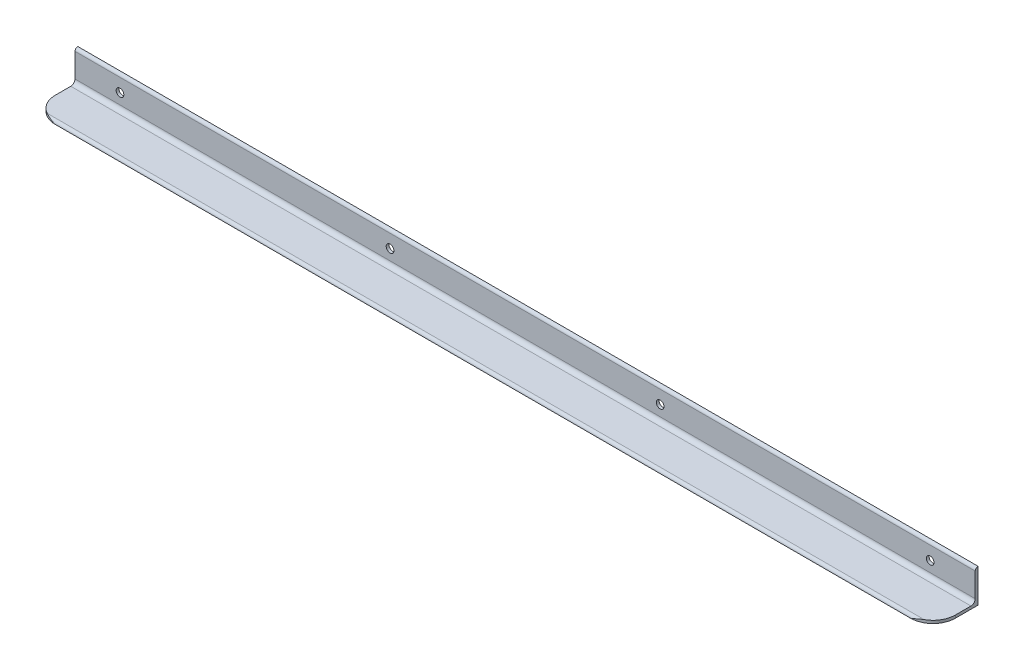
SolidWorks part; units mm, degrees
ref_plane "Front Plane" through (0, 0, 0) normal (0, 0, 1) x (1, 0, 0)
ref_plane "Top Plane" through (0, 0, 0) normal (0, 1, 0) x (1, 0, 0)
ref_plane "Right Plane" through (0, 0, 0) normal (1, 0, 0) x (0, 0, -1)
sketch "Sketch1" plane through (0, 0, 0) normal (0, 0, 1) x (1, 0, 0)
  line L0 (-508, 0) -> (508, 0)
  point P4 (0, 0)
  dimension "D1" = 1016
other "Al l angle (rounded ends) L2X1.5X0.125(1)"
ref_plane "Plane1" through (-508, 0, 0) normal (1, 0, 0) x (0, 1, 0)
sketch "Sketch12" plane through (-508, 0, 0) normal (1, 0, 0) x (0, 1, 0)
  line L0 (0, 0) -> (0, 50.8)
  line L1 (0, 50.8) -> (0.0051, 50.8)
  line L2 (3.175, 47.6301) -> (3.175, 7.9502)
  line L3 (7.9502, 3.175) -> (34.9301, 3.175)
  line L4 (38.1, 0.0051) -> (38.1, 0)
  line L5 (38.1, 0) -> (0, 0)
  arc A0 (38.1, 0.0051) -> (34.9301, 3.175) centre (34.9301, 0.0051) ccw
  arc A1 (0.0051, 50.8) -> (3.175, 47.6301) centre (0.0051, 47.6301) cw
  arc A2 (7.9502, 3.175) -> (3.175, 7.9502) centre (7.9502, 7.9502) cw
  circle A3 centre (0, 0) radius 3.175 construction
  point P10 (0, 25.4)
  point P14 (19.05, 0)
  point P15 (0, 0)
  dimension "D2" = 0.0051
  dimension "Radius_1" = 4.7752
  dimension "Radius_2" = 3.175
  dimension "D1" = 3.175
  dimension "V_leg" = 50.8
  dimension "H_leg" = 38.1
  dimension "Thickness" = 3.175
  dimension "Flat_wid" = 0.0051
sketch "Sketch13" plane through (0, 0, 0) normal (0, -1, 0) x (1, 0, 0)
  line L0 (-508, 50.8) -> (-508, 0) construction
  line L1 (508, 50.8) -> (-508, 50.8) construction
  line L2 (0, 0) -> (0, 111.0165) construction
  line L3 (-508, 50.8) -> (-508, 25.4)
  line L5 (-482.6, 50.8) -> (-508, 50.8)
  line L6 (508, 50.8) -> (508, 25.4)
  line L7 (482.6, 50.8) -> (508, 50.8)
  arc A0 (-482.6, 50.8) -> (-508, 25.4) centre (-482.6, 25.4) ccw
  arc A1 (482.6, 50.8) -> (508, 25.4) centre (482.6, 25.4) cw
  dimension "D1" = 25.4
extrude "Cut-Extrude1" cut sketch "Sketch13" against normal through all
sketch "Sketch14" plane through (0, 0, 0) normal (0, 0, -1) x (-1, 0, 0)
  line L0 (-508, 20) -> (508, 20) construction
  line L1 (-508, 0) -> (-508, 38.1) construction
  line L2 (508, 0) -> (508, 38.1) construction
  line L3 (508, 0) -> (-508, 0) construction
  line L4 (0, 0) -> (0, 94.7705) construction
  circle A0 centre (457.2, 20) radius 4.3497
  circle A1 centre (152.4, 20) radius 4.3497
  circle A2 centre (-152.4, 20) radius 4.3497
  circle A3 centre (-457.2, 20) radius 4.3497
  dimension "D2" = 4
  dimension "D3" = 304.8
  dimension "D4" = 8.6995
  dimension "D1" = 20
extrude "Cut-Extrude2" cut sketch "Sketch14" against normal through all
ref_plane "Plane2" through (0, 20, 0) normal (0, -1, 0) x (-1, 0, 0)
